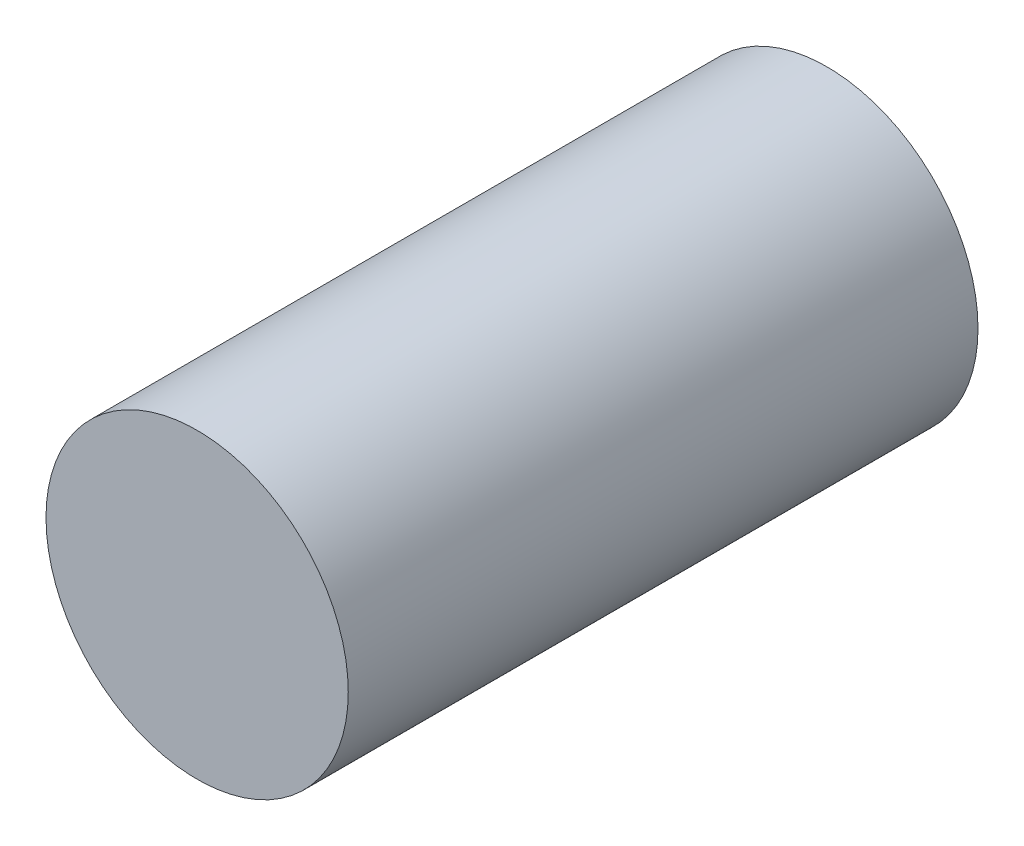
SolidWorks part; units mm, degrees
ref_plane "Front Plane" through (0, 0, 0) normal (0, 0, 1) x (1, 0, 0)
ref_plane "Top Plane" through (0, 0, 0) normal (0, 1, 0) x (1, 0, 0)
ref_plane "Right Plane" through (0, 0, 0) normal (1, 0, 0) x (0, 0, -1)
sketch "Sketch1" plane through (0, 0, 0) normal (0, 0, 1) x (1, 0, 0)
  circle A0 centre (0, 0) radius 6
  dimension "D1" = 12
extrude "Boss-Extrude1" add sketch "Sketch1" along normal blind 25
